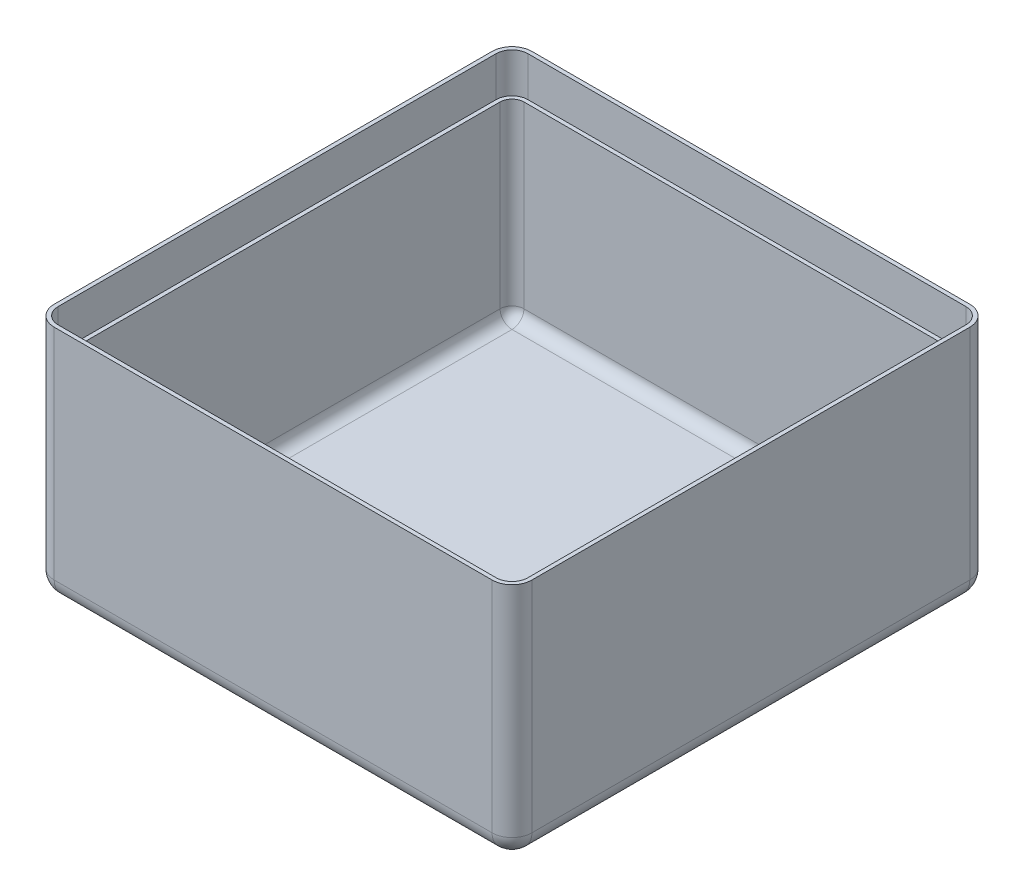
SolidWorks part; units mm, degrees
ref_plane "Front" through (0, 0, 0) normal (0, 0, 1) x (1, 0, 0)
ref_plane "Top" through (0, 0, 0) normal (0, 1, 0) x (1, 0, 0)
ref_plane "Right" through (0, 0, 0) normal (1, 0, 0) x (0, 0, -1)
sketch "Sketch1" plane through (0, 0, 0) normal (0, 1, 0) x (1, 0, 0)
  line L1 (0, 0) -> (60, 0)
  line L2 (0, 0) -> (0, 60)
  line L3 (0, 60) -> (60, 60)
  line L4 (60, 0) -> (60, 60)
  dimension "D1" = 60
  dimension "D2" = 60
extrude "Boss-Extrude1" add sketch "Sketch1" along normal blind 25
fillet "Fillet1" radius 2.5 8 edges at (30, 0, 0) (60, 0, -30) (30, 0, -60) (0, 0, -30) (0, 12.5, -60) (60, 12.5, -60) (60, 12.5, 0) (0, 12.5, 0)
shell "Shell1" thickness 1
sketch "Sketch2" plane through (0, 25, 0) normal (0, 1, 0) x (1, 0, 0)
  line L4 (57.5, 60) -> (2.5, 60)
  line L5 (0, 57.5) -> (0, 2.5)
  line L6 (2.5, 0) -> (57.5, 0)
  line L7 (60, 2.5) -> (60, 57.5)
  line L8 (57.5, 60) -> (2.5, 60)
  line L9 (0, 57.5) -> (0, 2.5)
  line L10 (2.5, 0) -> (57.5, 0)
  line L11 (60, 2.5) -> (60, 57.5)
  line L16 (57.5, 59.5) -> (2.5, 59.5)
  line L17 (0.5, 57.5) -> (0.5, 2.5)
  line L18 (2.5, 0.5) -> (57.5, 0.5)
  line L19 (59.5, 2.5) -> (59.5, 57.5)
  line L20 (57.5, 59.5) -> (2.5, 59.5)
  line L21 (0.5, 57.5) -> (0.5, 2.5)
  line L22 (2.5, 0.5) -> (57.5, 0.5)
  line L23 (59.5, 2.5) -> (59.5, 57.5)
  arc A4 (2.5, 60) -> (0, 57.5) centre (2.5, 57.5) ccw
  arc A5 (0, 2.5) -> (2.5, 0) centre (2.5, 2.5) ccw
  arc A6 (57.5, 0) -> (60, 2.5) centre (57.5, 2.5) ccw
  arc A7 (60, 57.5) -> (57.5, 60) centre (57.5, 57.5) ccw
  arc A8 (2.5, 60) -> (0, 57.5) centre (2.5, 57.5) ccw
  arc A9 (0, 2.5) -> (2.5, 0) centre (2.5, 2.5) ccw
  arc A10 (57.5, 0) -> (60, 2.5) centre (57.5, 2.5) ccw
  arc A11 (60, 57.5) -> (57.5, 60) centre (57.5, 57.5) ccw
  arc A16 (2.5, 59.5) -> (0.5, 57.5) centre (2.5, 57.5) ccw
  arc A17 (0.5, 2.5) -> (2.5, 0.5) centre (2.5, 2.5) ccw
  arc A18 (57.5, 0.5) -> (59.5, 2.5) centre (57.5, 2.5) ccw
  arc A19 (59.5, 57.5) -> (57.5, 59.5) centre (57.5, 57.5) ccw
  arc A20 (2.5, 59.5) -> (0.5, 57.5) centre (2.5, 57.5) ccw
  arc A21 (0.5, 2.5) -> (2.5, 0.5) centre (2.5, 2.5) ccw
  arc A22 (57.5, 0.5) -> (59.5, 2.5) centre (57.5, 2.5) ccw
  arc A23 (59.5, 57.5) -> (57.5, 59.5) centre (57.5, 57.5) ccw
  dimension "D1" = 0
  dimension "D2" = 0.5
extrude "Boss-Extrude2" add sketch "Sketch2" along normal blind 5
